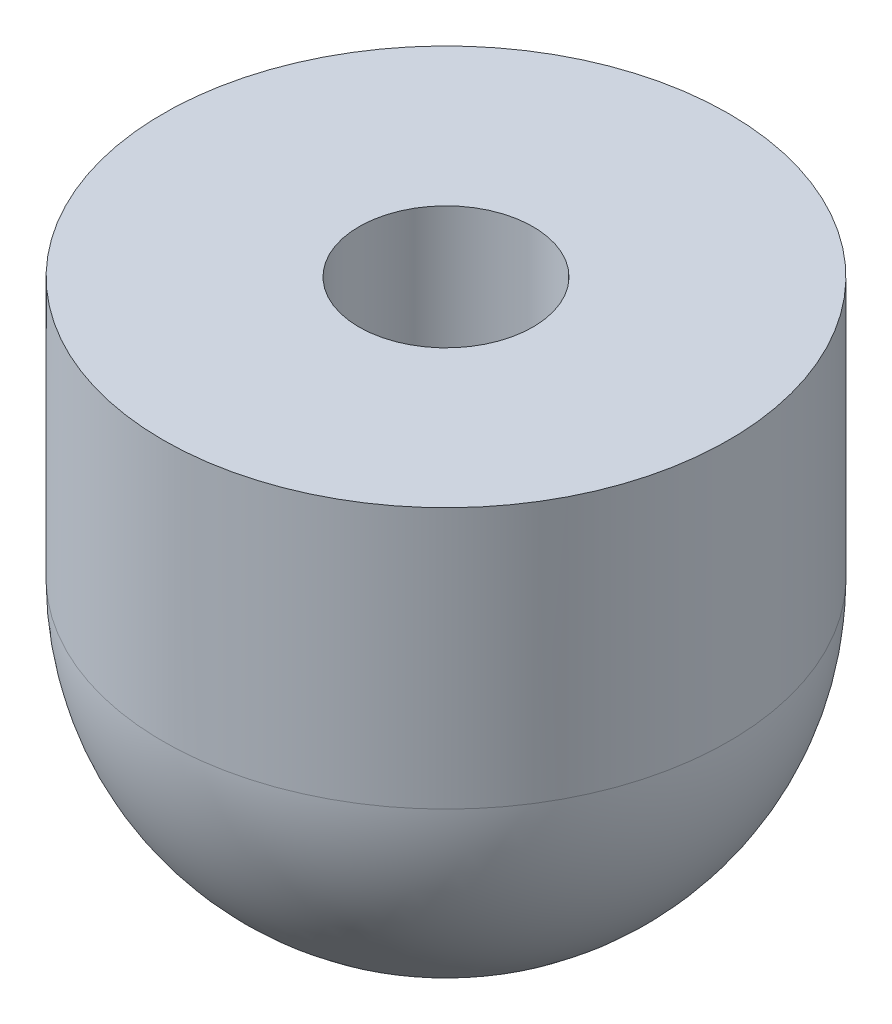
SolidWorks part; units mm, degrees
ref_plane "Front Plane" through (0, 0, 0) normal (0, 0, 1) x (1, 0, 0)
ref_plane "Top Plane" through (0, 0, 0) normal (0, 1, 0) x (1, 0, 0)
ref_plane "Right Plane" through (0, 0, 0) normal (1, 0, 0) x (0, 0, -1)
sketch "Sketch1" plane through (0, 0, 0) normal (0, 1, 0) x (1, 0, 0)
  circle A0 centre (0, 0) radius 13
  dimension "D1" = 26
extrude "Boss-Extrude1" add sketch "Sketch1" along normal blind 25
sketch "Sketch2" plane through (0, 25, 0) normal (0, 1, 0) x (1, 0, 0)
  circle A0 centre (0, 0) radius 4
  dimension "D1" = 8
extrude "Cut-Extrude1" cut sketch "Sketch2" against normal blind 8
sketch "Sketch4" plane through (0, 0, 0) normal (0, 0, 1) x (1, 0, 0)
  line L0 (-13, 25) -> (-13, 0) construction
  line L1 (13, 0) -> (13, 25) construction
  line L2 (-13, 13) -> (-13, -5.9582)
  line L3 (-13, -5.9582) -> (0, -5.9582)
  line L4 (0, -5.9582) -> (0, 0)
  line L6 (-13, 13) -> (-17.3684, 13)
  line L7 (-13, 13) -> (-13, -5.9582)
  line L8 (-13, -5.9582) -> (-17.3684, -5.9582)
  line L9 (-17.3684, 13) -> (-17.3684, -5.9582)
  arc A0 (-13, 13) -> (13, 13) centre (0, 13) ccw
revolve "Cut-Revolve1" cut sketch "Sketch4" angle 360 about L4
